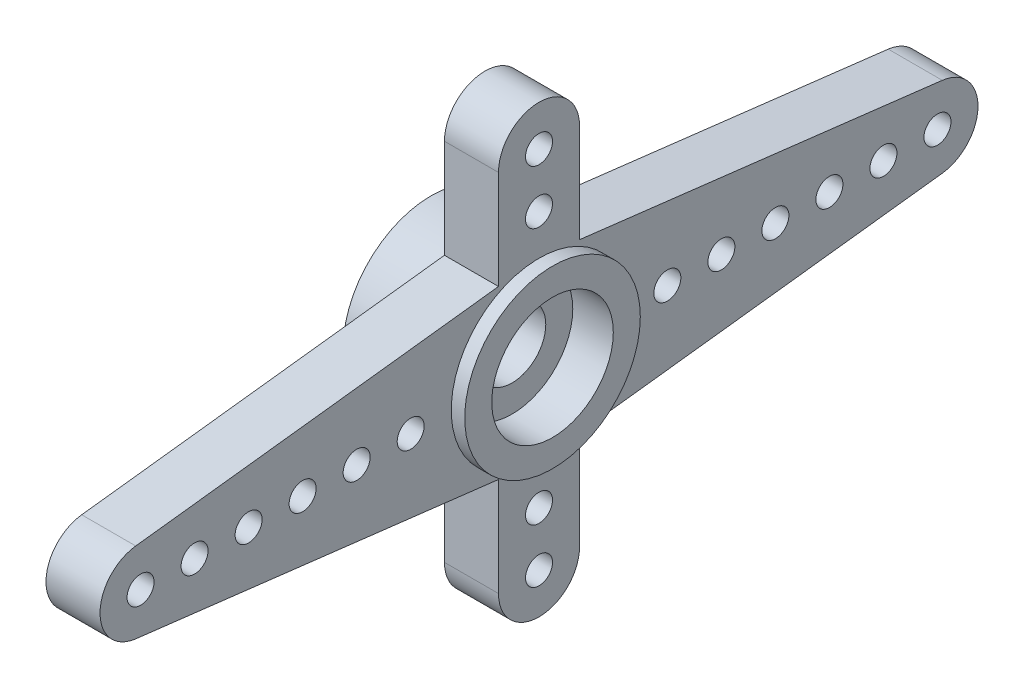
SolidWorks part; units mm, degrees
ref_plane "前视基准面" through (0, 0, 0) normal (0, 0, 1) x (1, 0, 0)
ref_plane "上视基准面" through (0, 0, 0) normal (0, 1, 0) x (1, 0, 0)
ref_plane "右视基准面" through (0, 0, 0) normal (1, 0, 0) x (0, 0, -1)
sketch "草图1" plane through (0, 0, 0) normal (1, 0, 0) x (0, 0, -1)
  line L0 (0, 0) -> (0, 50000) construction
  line L1 (0, 0) -> (-50000, 0) construction
  line L2 (-14.928, 1.4894) -> (-1.5, 3.0939)
  line L3 (1.5, -6.75) -> (1.5, -3.0939)
  line L4 (-1.5, -6.75) -> (-1.5, -3.0939)
  line L5 (14.928, 1.4894) -> (1.5, 3.0939)
  line L6 (-1.5, 6.75) -> (-1.5, 3.0939)
  line L7 (1.5, 6.75) -> (1.5, 3.0939)
  line L8 (14.928, -1.4894) -> (1.5, -3.0939)
  line L9 (-14.928, -1.4894) -> (-1.5, -3.0939)
  circle A0 centre (0, 0) radius 3.25
  circle A1 centre (4.75, 0) radius 0.5
  circle A2 centre (6.75, 0) radius 0.5
  circle A3 centre (8.75, 0) radius 0.5
  circle A4 centre (10.75, 0) radius 0.5
  circle A5 centre (12.75, 0) radius 0.5
  circle A6 centre (14.75, 0) radius 0.5
  circle A7 centre (-14.75, 0) radius 0.5
  circle A8 centre (-12.75, 0) radius 0.5
  circle A9 centre (-10.75, 0) radius 0.5
  circle A10 centre (-8.75, 0) radius 0.5
  circle A11 centre (-6.75, 0) radius 0.5
  circle A12 centre (-4.75, 0) radius 0.5
  circle A13 centre (0, 4.75) radius 0.5
  circle A14 centre (0, 6.75) radius 0.5
  circle A15 centre (0, -4.75) radius 0.5
  circle A16 centre (0, -6.75) radius 0.5
  arc A17 (-14.928, 1.4894) -> (-14.928, -1.4894) centre (-14.75, 0) ccw
  arc A18 (1.5, 6.75) -> (-1.5, 6.75) centre (0, 6.75) ccw
  arc A19 (1.5, -6.75) -> (-1.5, -6.75) centre (0, -6.75) cw
  arc A20 (14.928, 1.4894) -> (14.928, -1.4894) centre (14.75, 0) cw
  dimension "D1" = 6.5
  dimension "D2" = 1
  dimension "D3" = 4.75
  dimension "D5" = 4.75
  dimension "D7" = 1
  dimension "D8" = 1
  dimension "D9" = 1
  dimension "D6" = 2
  dimension "D4" = 6
extrude "凸台-拉伸1" add sketch "草图1" along normal blind 2
sketch "草图2" plane through (2, 0, 0) normal (1, 0, 0) x (0, 0, -1)
  circle A0 centre (0, 0) radius 3.25
  circle A1 centre (0, 0) radius 1.25
  dimension "D1" = 2.5
extrude "凸台-拉伸2" add sketch "草图2" against normal blind 2
sketch "草图3" plane through (0, 0, 0) normal (-1, 0, 0) x (0, 0, 1)
  circle A0 centre (0, 0) radius 3.25
  circle A1 centre (0, 0) radius 2.25
  dimension "D1" = 6.5
  dimension "D2" = 1
extrude "凸台-拉伸3" add sketch "草图3" along normal blind 2
sketch "草图4" plane through (2, 0, 0) normal (1, 0, 0) x (0, 0, -1)
  circle A0 centre (0, 0) radius 3.25
  circle A1 centre (0, 0) radius 2.25
  dimension "D1" = 6.5
  dimension "D2" = 1
extrude "凸台-拉伸5" add sketch "草图4" along normal blind 0.5
sketch "草图5" plane through (2, 0, 0) normal (1, 0, 0) x (0, 0, -1)
  circle A0 centre (0, 0) radius 2.25
  circle A1 centre (0, 0) radius 1.25
extrude "切除-拉伸1" cut sketch "草图5" against normal blind 1
